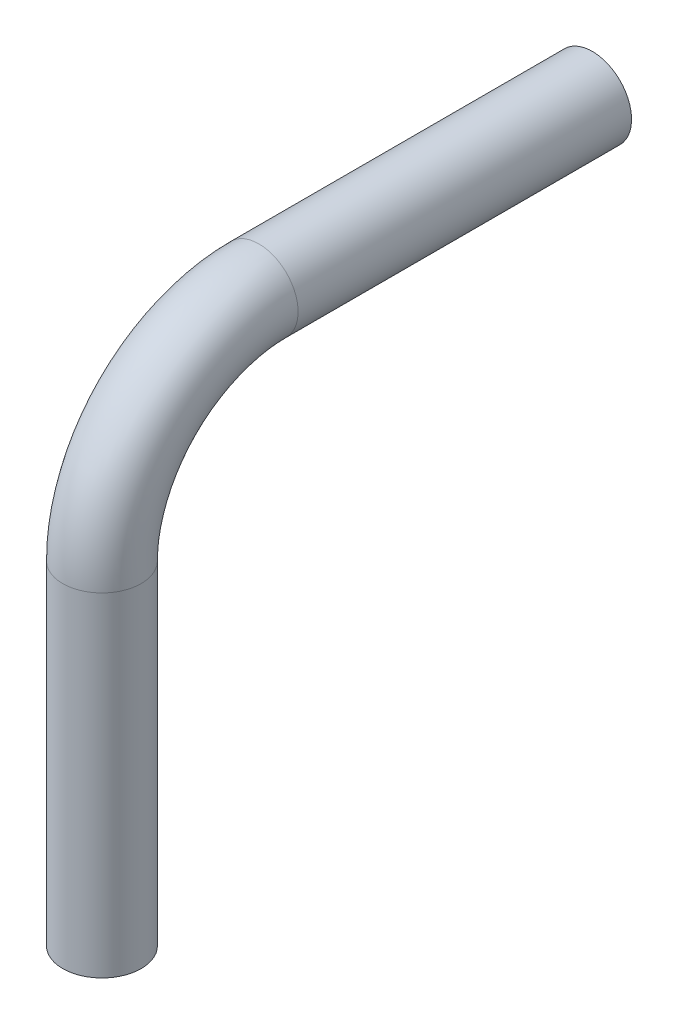
SolidWorks part; units mm, degrees
ref_plane "Спереди" through (0, 0, 0) normal (0, 0, 1) x (1, 0, 0)
ref_plane "Сверху" through (0, 0, 0) normal (0, 1, 0) x (1, 0, 0)
ref_plane "Справа" through (0, 0, 0) normal (1, 0, 0) x (0, 0, -1)
sketch "Эскиз1" plane through (0, 0, 0) normal (1, 0, 0) x (0, 0, -1)
  line L0 (1.6, 0) -> (5, 0)
  line L1 (0, -1.6) -> (0, -5)
  arc A0 (0, -1.6) -> (1.6, 0) centre (1.6, -1.6) cw
  point P6 (0, 0)
  dimension "D1" = 1.6
ref_plane "Плоскость1" through (0, 0, -5) normal (0, 0, -1) x (-1, 0, 0)
sketch "Эскиз2" plane through (0, 0, -5) normal (0, 0, -1) x (-1, 0, 0)
  circle A0 centre (0, 0) radius 0.4
sweep "По траектории1" add profiles "Эскиз2" path "Эскиз1"
